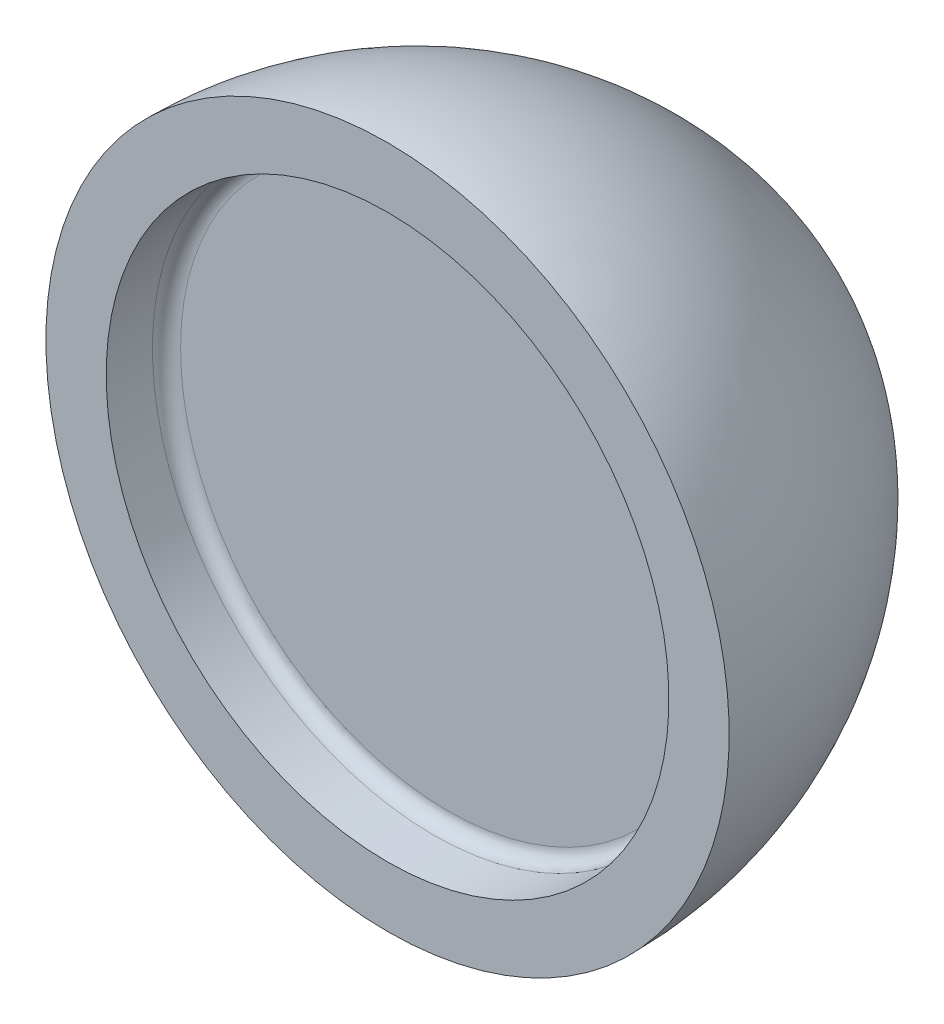
SolidWorks part; units mm, degrees
ref_plane "Front Plane" through (0, 0, 0) normal (0, 0, 1) x (1, 0, 0)
ref_plane "Top Plane" through (0, 0, 0) normal (0, 1, 0) x (1, 0, 0)
ref_plane "Right Plane" through (0, 0, 0) normal (1, 0, 0) x (0, 0, -1)
sketch "Sketch1" plane through (0, 0, 0) normal (1, 0, 0) x (0, 0, -1)
  line L0 (3, 0) -> (20, 0)
  line L3 (3, 0) -> (26.2537, 0) construction
  line L4 (0, 17) -> (0, 14)
  line L5 (0, 14) -> (3, 14)
  line L6 (0, 17) -> (29.4538, 17) construction
  line L7 (3, 14) -> (3, 0)
  line L8 (0, 0) -> (0, 11.0994) construction
  line L9 (0, 0) -> (-6.9305, 0) construction
  arc A2 (20, 0) -> (0, 17) centre (0, -3.2647) ccw
  dimension "D1" = 17
  dimension "D2" = 20
  dimension "D3" = 3
  dimension "D4" = 3
revolve "Revolve1" add sketch "Sketch1" angle 360 about L3
fillet "Fillet1" radius 0.7 1 edges at (0, -14, -3)
